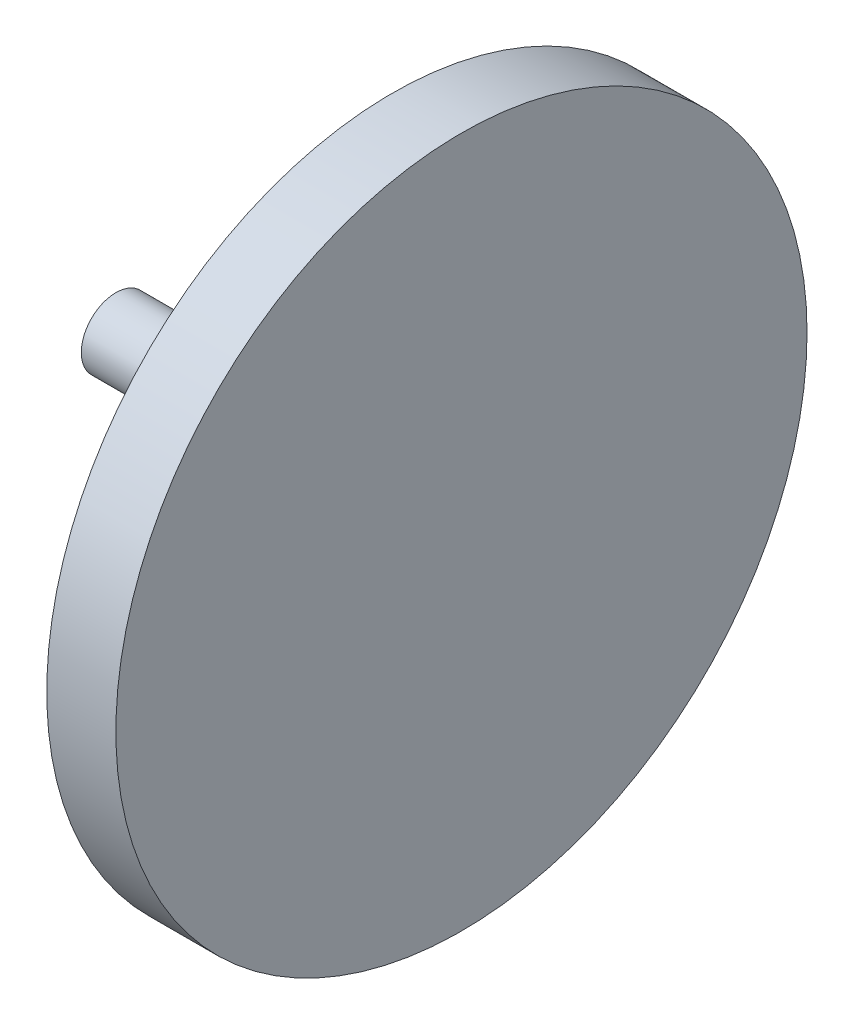
SolidWorks part; units mm, degrees
material "HYPALON"
ref_plane "Front Plane" through (0, 0, 0) normal (0, 0, 1) x (1, 0, 0)
ref_plane "Top Plane" through (0, 0, 0) normal (0, 1, 0) x (1, 0, 0)
ref_plane "Right Plane" through (0, 0, 0) normal (1, 0, 0) x (0, 0, -1)
sketch "Sketch1" plane through (0, 0, 0) normal (1, 0, 0) x (0, 0, -1)
  circle A0 centre (0, 0) radius 2.5
  dimension "D1" = 5
extrude "Boss-Extrude1" add sketch "Sketch1" along normal blind 15 and the other way blind 5
sketch "Sketch2" plane through (15, 0, 0) normal (1, 0, 0) x (0, 0, -1)
  circle A0 centre (0, 0) radius 25
  dimension "D1" = 50
extrude "Boss-Extrude2" add sketch "Sketch2" along normal blind 5
